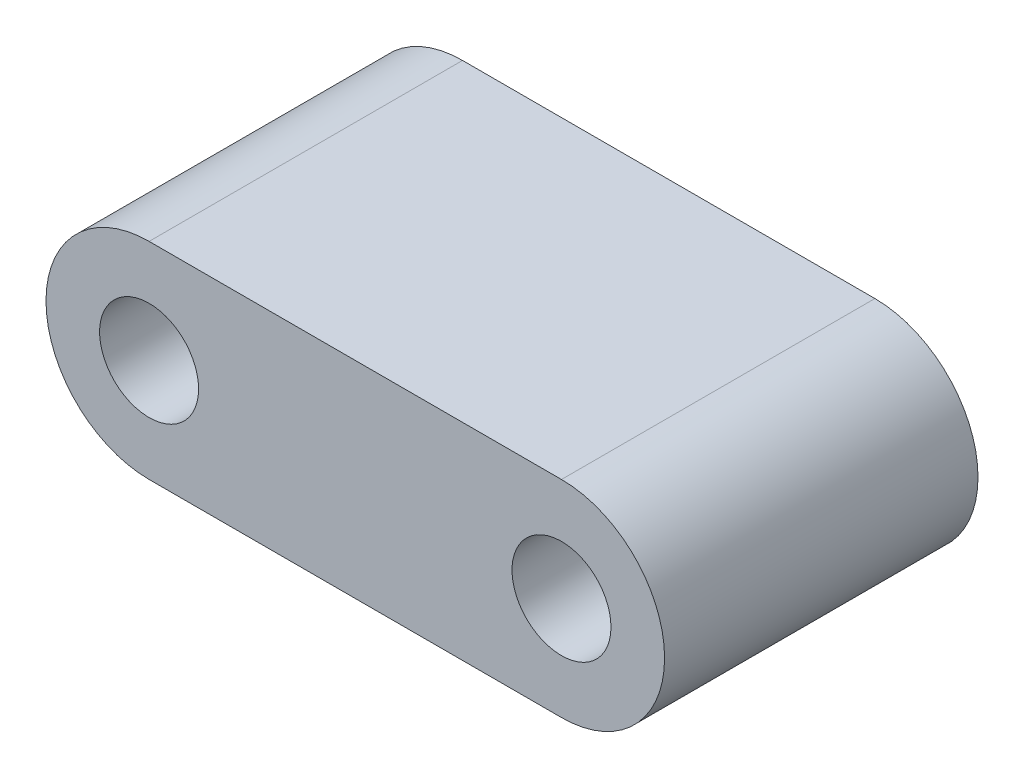
SolidWorks part; units mm, degrees
ref_plane "Front Plane" through (0, 0, 0) normal (0, 0, 1) x (1, 0, 0)
ref_plane "Top Plane" through (0, 0, 0) normal (0, 1, 0) x (1, 0, 0)
ref_plane "Right Plane" through (0, 0, 0) normal (1, 0, 0) x (0, 0, -1)
sketch "Sketch1" plane through (0, 0, 0) normal (0, 0, 1) x (1, 0, 0)
  line L0 (0, 0) -> (50, 0) construction
  line L1 (0, 12.5) -> (50, 12.5)
  line L2 (0, -12.5) -> (50, -12.5)
  arc A0 (0, 12.5) -> (0, -12.5) centre (0, 0) ccw
  arc A1 (50, -12.5) -> (50, 12.5) centre (50, 0) ccw
  circle A2 centre (0, 0) radius 6
  circle A3 centre (50, 0) radius 6
  point P3 (25, 0)
  dimension "D2" = 12.5
  dimension "D3" = 12
  dimension "D4" = 12
  dimension "D1" = 50
extrude "Boss-Extrude1" add sketch "Sketch1" along normal mid plane 38
sketch "Sketch2" plane through (0, -12.5, 0) normal (0, -1, 0) x (1, 0, 0)
  circle A0 centre (25, 0) radius 6
  dimension "D1" = 12
  dimension "D2" = 25
extrude "Cut-Extrude1" cut sketch "Sketch2" against normal blind 12.5
